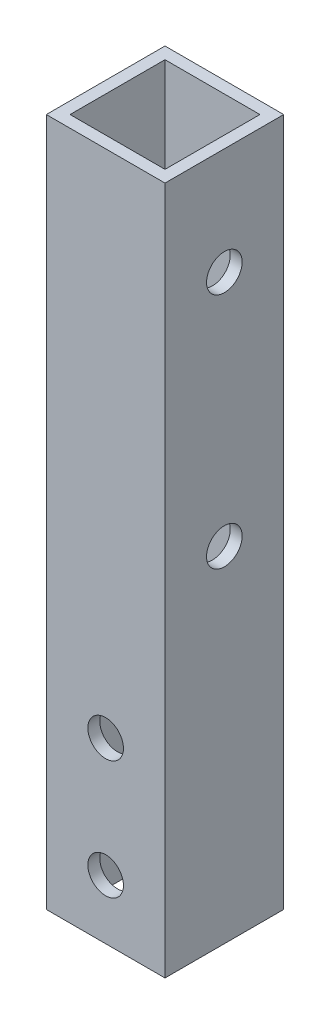
SolidWorks part; units mm, degrees
material "氧化铝"
ref_plane "前视基准面" through (0, 0, 0) normal (0, 0, 1) x (1, 0, 0)
ref_plane "上视基准面" through (0, 0, 0) normal (0, 1, 0) x (1, 0, 0)
ref_plane "右视基准面" through (0, 0, 0) normal (1, 0, 0) x (0, 0, -1)
other "Configuration Table"
sketch "草图1" plane through (0, 0, 0) normal (0, 1, 0) x (1, 0, 0)
  line L1 (-4, 4) -> (4, 4)
  line L2 (-4, 4) -> (-4, -4)
  line L3 (-4, -4) -> (4, -4)
  line L4 (4, 4) -> (4, -4)
  line L5 (-4, 4) -> (4, -4) construction
  line L6 (-4, -4) -> (4, 4) construction
  line L7 (-5, 5) -> (5, 5)
  line L8 (-5, 5) -> (-5, -5)
  line L9 (-5, -5) -> (5, -5)
  line L10 (5, 5) -> (5, -5)
  line L11 (-5, 5) -> (5, -5) construction
  line L12 (-5, -5) -> (5, 5) construction
  point P0 (0, 0)
  point P6 (0, 0)
  dimension "D1" = 1
  dimension "D2" = 1
  dimension "D3" = 10
  dimension "D4" = 10
extrude "凸台-拉伸1" add sketch "草图1" along normal blind 58
sketch "草图2" plane through (0, 0, 5) normal (0, 0, 1) x (1, 0, 0)
  line L0 (0, 0) -> (0, 58) construction
  line L1 (-5, 58) -> (5, 58) construction
  line L2 (-5, 0) -> (5, 0) construction
  circle A0 centre (0, 5) radius 1.5
  circle A1 centre (0, 15) radius 1.5
  dimension "D3" = 3
  dimension "D1" = 10
  dimension "D2" = 5
extrude "切除-拉伸1" cut sketch "草图2" against normal blind 30
sketch "草图3" plane through (-5, 0, 0) normal (-1, 0, 0) x (0, 0, 1)
  line L0 (0, 0) -> (0, 58) construction
  line L1 (-5, 0) -> (5, 0) construction
  line L2 (-5, 58) -> (5, 58) construction
  circle A0 centre (0, 49) radius 1.5
  circle A1 centre (0, 29) radius 1.5
  dimension "D3" = 3
  dimension "D1" = 20
  dimension "D2" = 9
extrude "切除-拉伸2" cut sketch "草图3" against normal blind 30
